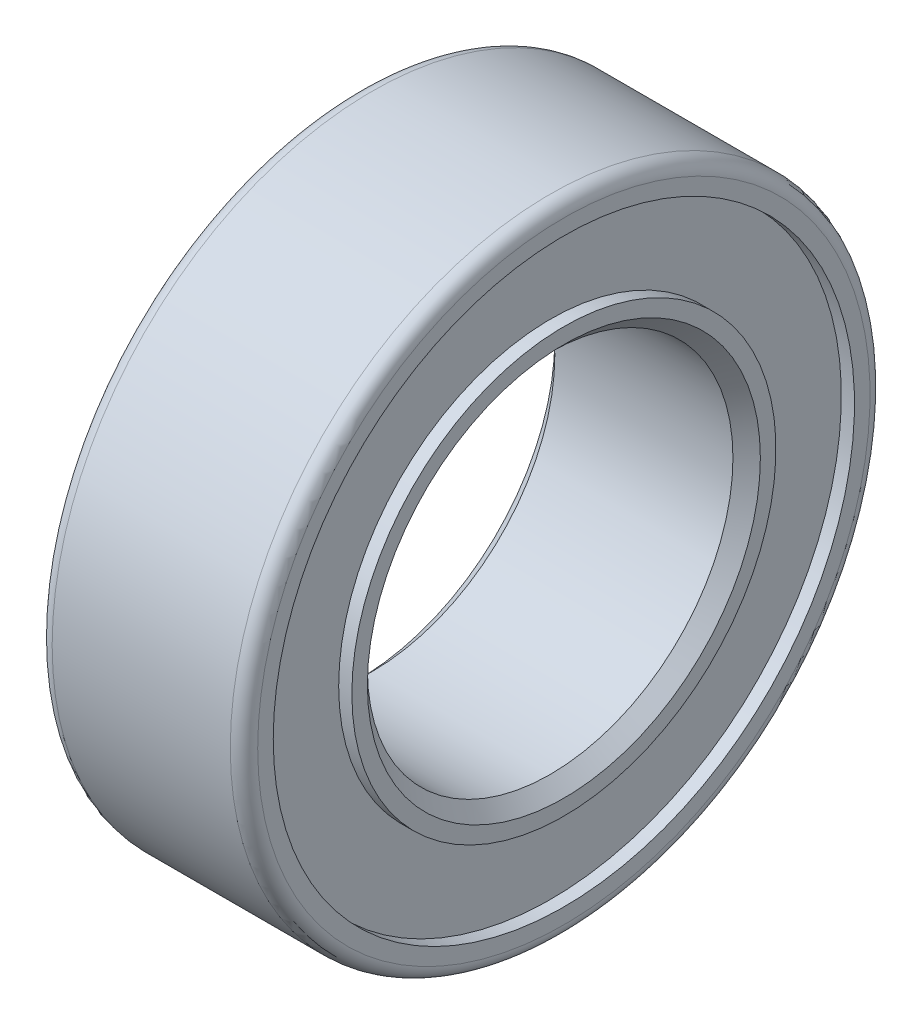
SolidWorks part; units mm, degrees
ref_plane "Front Plane" through (0, 0, 0) normal (0, 0, 1) x (1, 0, 0)
ref_plane "Top Plane" through (0, 0, 0) normal (0, 1, 0) x (1, 0, 0)
ref_plane "Right Plane" through (0, 0, 0) normal (1, 0, 0) x (0, 0, -1)
ref_plane "Plane4" through (0, 0, 0) normal (0, 0, -1) x (-1, 0, 0)
sketch "Sketch1" plane through (0, 0, 0) normal (0, 0, -1) x (-1, 0, 0)
  line L0 (-3.5702, 6.8263) -> (-3.094, 6.35)
  line L1 (-3.094, 6.35) -> (3.094, 6.35)
  line L2 (3.094, 6.35) -> (3.5702, 6.8262)
  line L3 (3.5702, 6.8262) -> (3.5702, 7.366)
  line L4 (3.5702, 7.366) -> (3.113, 7.366)
  line L5 (3.113, 7.366) -> (3.113, 10.0965)
  line L6 (3.113, 10.0965) -> (3.5702, 10.0965)
  line L7 (3.5702, 10.0965) -> (3.5702, 10.6363)
  line L8 (3.094, 11.1125) -> (-3.094, 11.1125)
  line L9 (-3.5702, 10.6363) -> (-3.5702, 10.0965)
  line L10 (-3.5702, 10.0965) -> (-3.113, 10.0965)
  line L11 (-3.113, 10.0965) -> (-3.113, 7.366)
  line L12 (-3.113, 7.366) -> (-3.5702, 7.366)
  line L13 (-3.5702, 7.366) -> (-3.5702, 6.8263)
  line L14 (-3.5715, 0) -> (3.5715, 0) construction
  arc A0 (3.5702, 10.6363) -> (3.094, 11.1125) centre (3.094, 10.6363) ccw
  arc A1 (-3.094, 11.1125) -> (-3.5702, 10.6363) centre (-3.094, 10.6363) ccw
revolve "Revolve1" add sketch "Sketch1" angle 360 about L14
